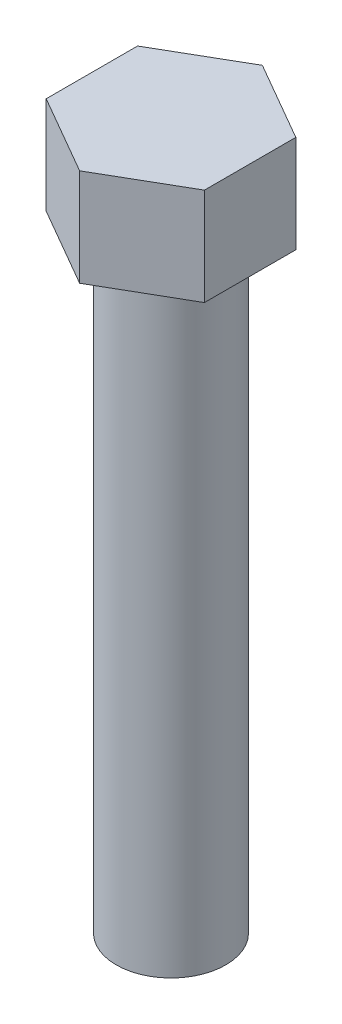
SolidWorks part; units mm, degrees
ref_plane "Front Plane" through (0, 0, 0) normal (0, 0, 1) x (1, 0, 0)
ref_plane "Top Plane" through (0, 0, 0) normal (0, 1, 0) x (1, 0, 0)
ref_plane "Right Plane" through (0, 0, 0) normal (1, 0, 0) x (0, 0, -1)
sketch "Sketch1" plane through (0, 0, 0) normal (0, 1, 0) x (1, 0, 0)
  circle A0 centre (0, 0) radius 2.25
  dimension "D1" = 4.5
extrude "Boss-Extrude1" add sketch "Sketch1" along normal blind 25
sketch "Sketch2" plane through (0, 25, 0) normal (0, 1, 0) x (1, 0, 0)
  line L1 (3.25, -1.8764) -> (3.25, 1.8764)
  line L2 (3.25, 1.8764) -> (0, 3.7528)
  line L3 (0, 3.7528) -> (-3.25, 1.8764)
  line L4 (-3.25, 1.8764) -> (-3.25, -1.8764)
  line L5 (-3.25, -1.8764) -> (0, -3.7528)
  line L6 (0, -3.7528) -> (3.25, -1.8764)
  circle A0 centre (0, 0) radius 3.25 construction
  dimension "D1" = 6.5
extrude "Boss-Extrude2" add sketch "Sketch2" along normal blind 4
